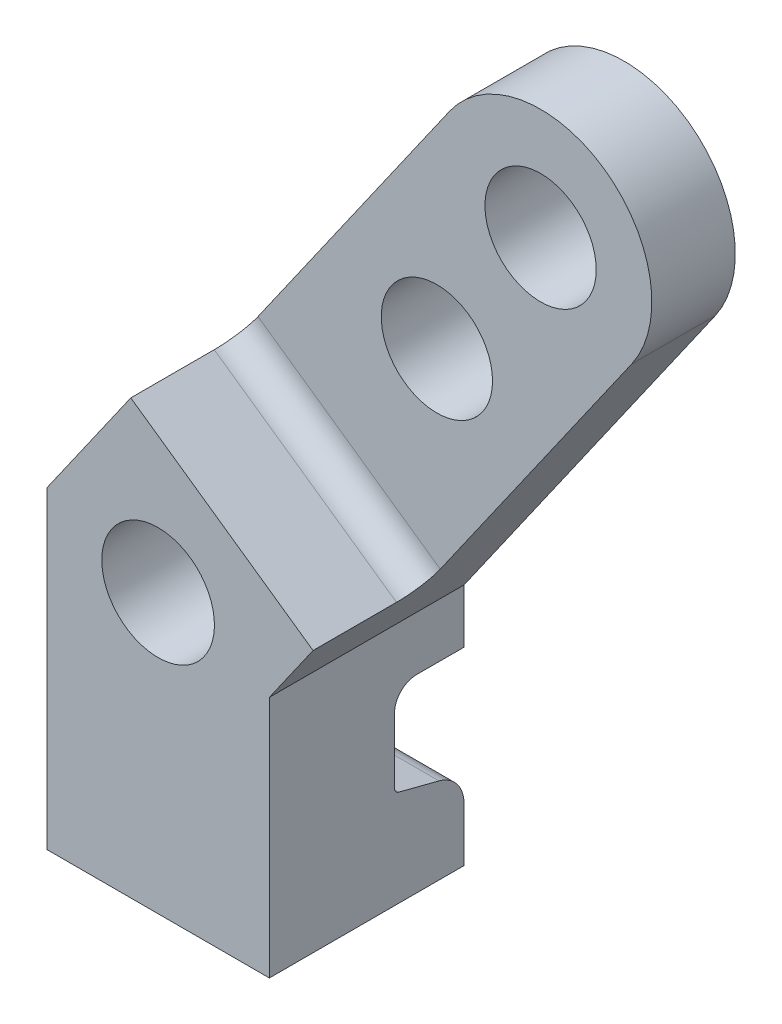
SolidWorks part; units mm, degrees
ref_plane "前视基准面" through (0, 0, 0) normal (0, 0, 1) x (1, 0, 0)
ref_plane "上视基准面" through (0, 0, 0) normal (0, 1, 0) x (1, 0, 0)
ref_plane "右视基准面" through (0, 0, 0) normal (1, 0, 0) x (0, 0, -1)
sketch "草图1" plane through (0, 0, 0) normal (0, 0, 1) x (1, 0, 0)
  line L0 (0, -1000) -> (0, 49000) construction
  line L1 (0, 0) -> (28678.8218, 40957.6022) construction
  line L2 (-1000, 0) -> (49000, 0) construction
  line L3 (64.7419, 162.1989) -> (-40, 12.612)
  line L4 (130.2741, 116.3128) -> (40, -12.612)
  line L5 (-40, 12.612) -> (-40, -100)
  line L6 (-40, -100) -> (40, -100)
  line L7 (40, -100) -> (40, -12.612)
  circle A0 centre (0, 0) radius 20.25
  circle A1 centre (97.508, 139.2558) radius 20
  circle A2 centre (60.2255, 86.011) radius 20
  arc A3 (64.7419, 162.1989) -> (130.2741, 116.3128) centre (97.508, 139.2558) cw
  dimension "D2" = 40.5
  dimension "D3" = 40
  dimension "D4" = 40
  dimension "D7" = 40
  dimension "D1" = 55
  dimension "D5" = 105
  dimension "D6" = 170
  dimension "D8" = 40
  dimension "D9" = 40
  dimension "D10" = 100
extrude "凸台-拉伸1" add sketch "草图1" along normal blind 70
sketch "草图2" plane through (0, 0, 0) normal (0, 0, 1) x (1, 0, 0)
  line L0 (-9.823, 55.7091) -> (55.7091, 9.823)
  line L1 (64.7419, 162.1989) -> (-40, 12.612) construction
  line L2 (40, -12.612) -> (130.2741, 116.3128) construction
  line L3 (55.7091, 9.823) -> (170.4244, 173.6534)
  line L4 (170.4244, 173.6534) -> (104.8923, 219.5395)
  line L5 (104.8923, 219.5395) -> (-9.823, 55.7091)
  circle A0 centre (97.508, 139.2558) radius 20 construction
  dimension "D1" = 130
  dimension "D2" = 200
extrude "切除-拉伸1" cut sketch "草图2" along normal blind 40
sketch "草图3" plane through (-40, 0, 0) normal (-1, 0, 0) x (0, 0, 1)
  line L0 (70, -32) -> (45, -32)
  line L1 (70, 12.612) -> (70, -100) construction
  line L2 (45, -32) -> (45, -65)
  line L3 (45, -65) -> (70, -71.455)
  line L4 (70, -71.455) -> (70, -32)
  line L5 (45, -65) -> (122.4597, -65) construction
  line L6 (45, -65) -> (122.4597, -85) construction
  dimension "D1" = 32
  dimension "D2" = 33
  dimension "D3" = 25
  dimension "D4" = 20
  dimension "D5" = 80
extrude "切除-拉伸2" cut sketch "草图3" against normal through all
fillet "圆角1" radius 12 1 edges at (0, -71.455, 70)
fillet "圆角2" radius 2 1 edges at (0, -65, 45)
fillet "圆角3" radius 8 1 edges at (0, -32, 45)
fillet "圆角4" radius 10 1 edges at (22.9431, 32.7661, 40)
mirror "镜向1" about plane through (97.508, 139.2558, 0) normal (0, 0, -1) of bodies 108
sketch "草图5" plane through (-40, 0, 0) normal (-1, 0, 0) x (0, 0, 1)
  line L0 (70, -100) -> (-70, -100) construction
  line L1 (0, 200) -> (70, 200)
  line L2 (0, 200) -> (0, -100)
  line L3 (0, -100) -> (70, -100)
  line L4 (70, 200) -> (70, -100)
  line L5 (70, -80.7501) -> (70, -100) construction
  dimension "D1" = 300
extrude "切除-拉伸4" cut sketch "草图5" against normal through all
